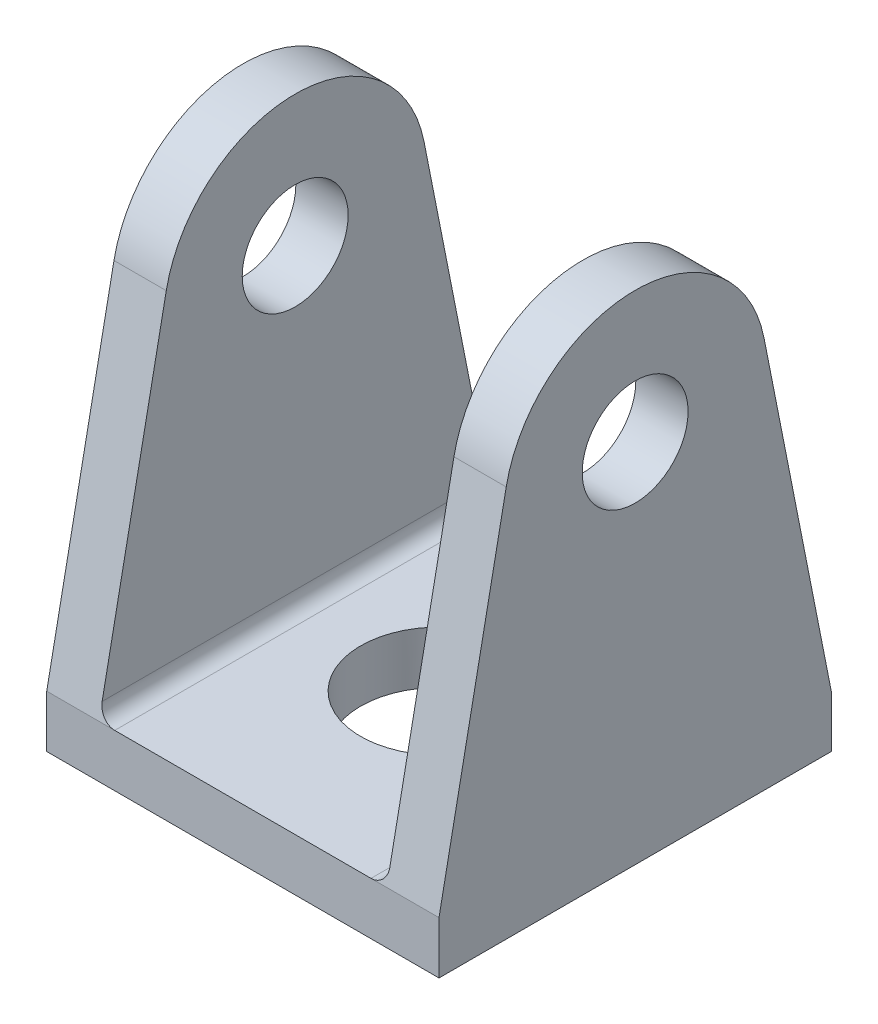
SolidWorks part; units mm, degrees
ref_plane "Plan de face" through (0, 0, 0) normal (0, 0, 1) x (1, 0, 0)
ref_plane "Plan de dessus" through (0, 0, 0) normal (0, 1, 0) x (1, 0, 0)
ref_plane "Plan de droite" through (0, 0, 0) normal (1, 0, 0) x (0, 0, -1)
sketch "Esquisse1" plane through (0, 0, 0) normal (0, 1, 0) x (1, 0, 0)
  line L0 (0, 0) -> (75, 75) construction
  line L1 (0, 0) -> (75, 0)
  line L2 (0, 0) -> (0, 75)
  line L3 (0, 75) -> (75, 75)
  line L4 (75, 0) -> (75, 75)
  circle A0 centre (37.5, 37.5) radius 15
  dimension "D3" = 30
  dimension "D1" = 75
  dimension "D2" = 75
extrude "Boss.-Extru.2" add sketch "Esquisse1" along normal blind 10
sketch "Esquisse2" plane through (75, 0, 0) normal (1, 0, 0) x (0, 0, -1)
  line L0 (37.5, 0) -> (37.5, 199.2873) construction
  line L1 (0, 0) -> (75, 0) construction
  line L2 (37.5, 199.2873) -> (75, 10) construction
  line L3 (75, 10) -> (0, 10) construction
  line L4 (0, 10) -> (37.5, 199.2873) construction
  line L5 (63.1133, 70) -> (37.5, 70) construction
  line L6 (37.5, 70) -> (11.8867, 70) construction
  line L7 (62.146, 74.8827) -> (75, 10)
  line L8 (75, 10) -> (0, 10)
  line L9 (0, 10) -> (12.854, 74.8827)
  circle A0 centre (37.5, 70) radius 10.125
  arc A1 (62.146, 74.8827) -> (12.854, 74.8827) centre (37.5, 70) ccw
  dimension "D1" = 20.25
  dimension "D3" = 15
  dimension "D2" = 60
extrude "Boss.-Extru.3" add sketch "Esquisse2" against normal up to surface (75 mm away) up to face at (0, 5, -37.5)
sketch "Esquisse3" plane through (0, 0, 0) normal (0, 0, 1) x (1, 0, 0)
  line L0 (0, 10) -> (75, 10) construction
  line L1 (10, 10) -> (65, 10)
  line L2 (10, 10) -> (10, 132.4018)
  line L3 (10, 132.4018) -> (65, 132.4018)
  line L4 (65, 10) -> (65, 132.4018)
  line L5 (0, 10) -> (0, 74.8827) construction
  line L6 (75, 74.8827) -> (75, 10) construction
  dimension "D1" = 10
  dimension "D2" = 10
extrude "Enlèv. mat.-Extru.1" cut sketch "Esquisse3" against normal through all
fillet "Congé1" radius 3 2 edges at (65, 10, -37.5) (10, 10, -37.5)
